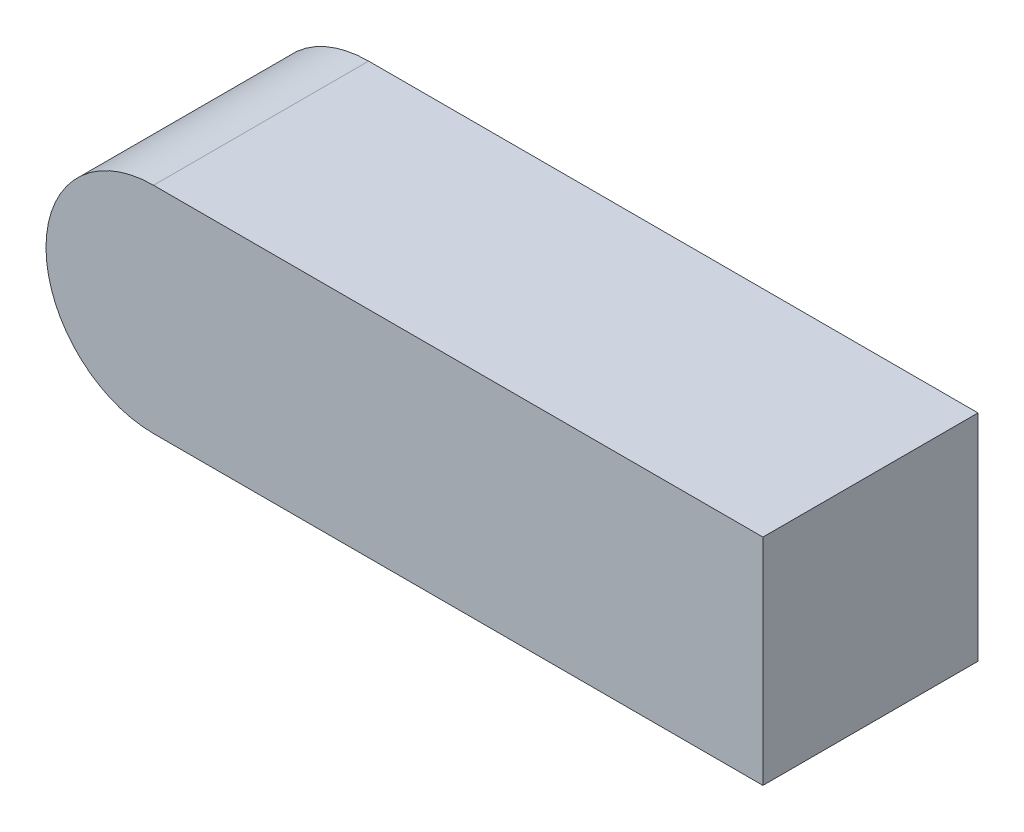
SolidWorks part; units mm, degrees
material "SUS304"
ref_plane "Front Plane" through (0, 0, 0) normal (0, 0, 1) x (1, 0, 0)
ref_plane "Top Plane" through (0, 0, 0) normal (0, 1, 0) x (1, 0, 0)
ref_plane "Right Plane" through (0, 0, 0) normal (1, 0, 0) x (0, 0, -1)
sketch "Sketch1" plane through (0, 0, 0) normal (0, 0, 1) x (1, 0, 0)
  line L0 (-17, 0) -> (0, 0) construction
  line L1 (-17, -3) -> (0, -3)
  line L2 (-17, 3) -> (0, 3)
  line L3 (0, 3) -> (0, -3)
  arc A0 (-17, -3) -> (-17, 3) centre (-17, 0) cw
  arc A1 (0, -3) -> (0, 3) centre (0, 0) ccw construction
  dimension "D3" = 20
  dimension "D1" = 3
  dimension "D2" = 3
extrude "Boss-Extrude1" add sketch "Sketch1" along normal blind 6
equation "\"Mass Kg\"= \"SW-Mass\""
